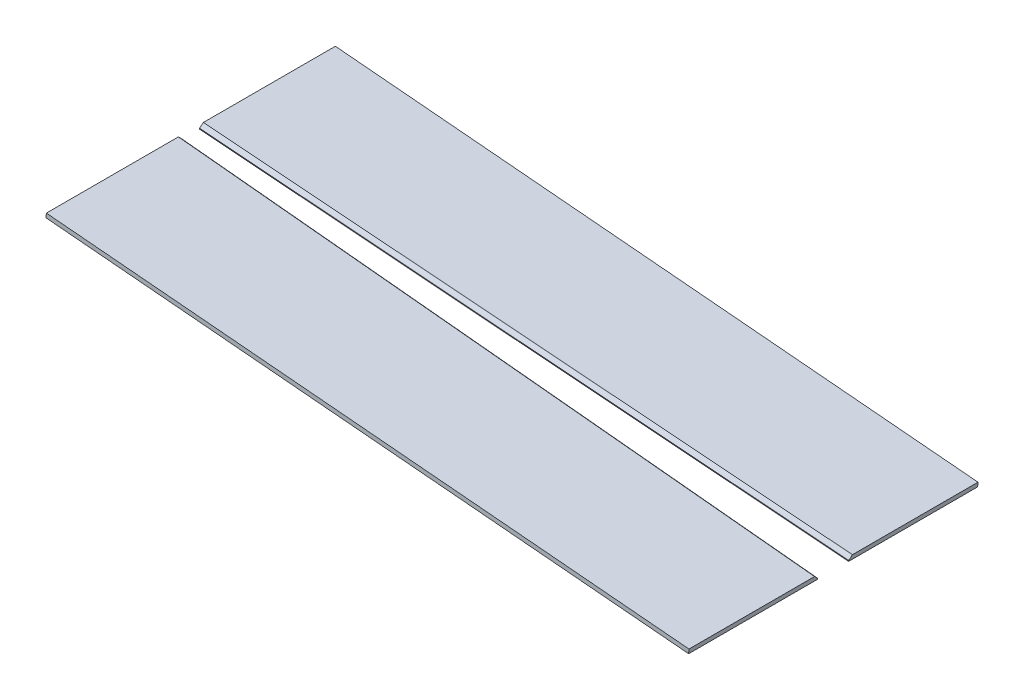
SolidWorks part; units mm, degrees
ref_plane "Front Plane" through (0, 0, 0) normal (0, 0, 1) x (1, 0, 0)
ref_plane "Top Plane" through (0, 0, 0) normal (0, 1, 0) x (1, 0, 0)
ref_plane "Right Plane" through (0, 0, 0) normal (1, 0, 0) x (0, 0, -1)
sketch "Sketch1" plane through (0, 0, 0) normal (0, 1, 0) x (1, 0, 0)
  line L0 (0, 83.7037) -> (0, -72.1487) construction
ref_plane "Plane1" through (0, 0, 0) normal (-0.0872, -0.9962, 0) x (0, 0, 1)
sketch "Sketch2" plane through (0, 0, 0) normal (-0.0872, -0.9962, 0) x (0, 0, 1)
  line L0 (0, 0) -> (0, 1664.8428) construction
  line L4 (-12, 600) -> (-18, 0)
  line L6 (12, 600) -> (18, 0)
  line L9 (-12, 600) -> (-168, 600) construction
  line L10 (-168, 600) -> (-168, 0)
  line L11 (-168, 0) -> (-18, 0)
  line L12 (12, 600) -> (168, 600) construction
  line L13 (168, 600) -> (168, 0)
  line L14 (168, 0) -> (18, 0)
  line L15 (-83.7037, 0) -> (72.1487, 0) construction
  line L16 (12, 600) -> (10.5, 750)
  line L17 (-12, 600) -> (-10.5, 750)
  line L18 (-168, 600) -> (-168, 750)
  line L19 (-168, 750) -> (-10.5, 750)
  line L20 (168, 600) -> (168, 750)
  line L21 (168, 750) -> (10.5, 750)
  line L22 (168, 450) -> (13.5, 450) construction
  line L23 (168, 300) -> (15, 300) construction
  line L24 (168, 150) -> (16.5, 150) construction
  dimension "D1" = 600
  dimension "D2" = 150
  dimension "D3" = 12
  dimension "D4" = 150
  dimension "D5" = 150
  dimension "D6" = 18
  dimension "D7" = 18
  dimension "D8" = 12
  dimension "D9" = 150
  dimension "D10" = 150
  dimension "D11" = 150
  dimension "D12" = 21
  dimension "D13" = 36
extrude "Boss-Extrude1" add sketch "Sketch2" against normal blind 5
chamfer "Chamfer1" distance 4 angle 45 1 edges at (-373.1372, 37.6644, -14.25)
chamfer "Chamfer2" distance 4 angle 45 1 edges at (-373.1372, 37.6644, 14.25)
sketch "Sketch3" plane through (0, 0, 0) normal (-0.0872, -0.9962, 0) x (0.9962, -0.0872, 0)
  line L0 (-750, 168) -> (-750, 10.5) construction
  line L2 (-500, 89.25) -> (-50, 89.25) construction
  line L3 (38.6913, 0) -> (-38.6913, 0) construction
  line L4 (-500, -89.25) -> (-50, -89.25) construction
  dimension "D1" = 250
  dimension "D2" = 450
sketch "Sketch4" plane through (0, 0, 0) normal (0, 1, 0) x (1, 0, 0)
  line L0 (0, 0) -> (-363.8071, 0) construction
ref_plane "Plane2" through (-750, 0, 0) normal (1, 0, 0) x (0, 0, -1)
